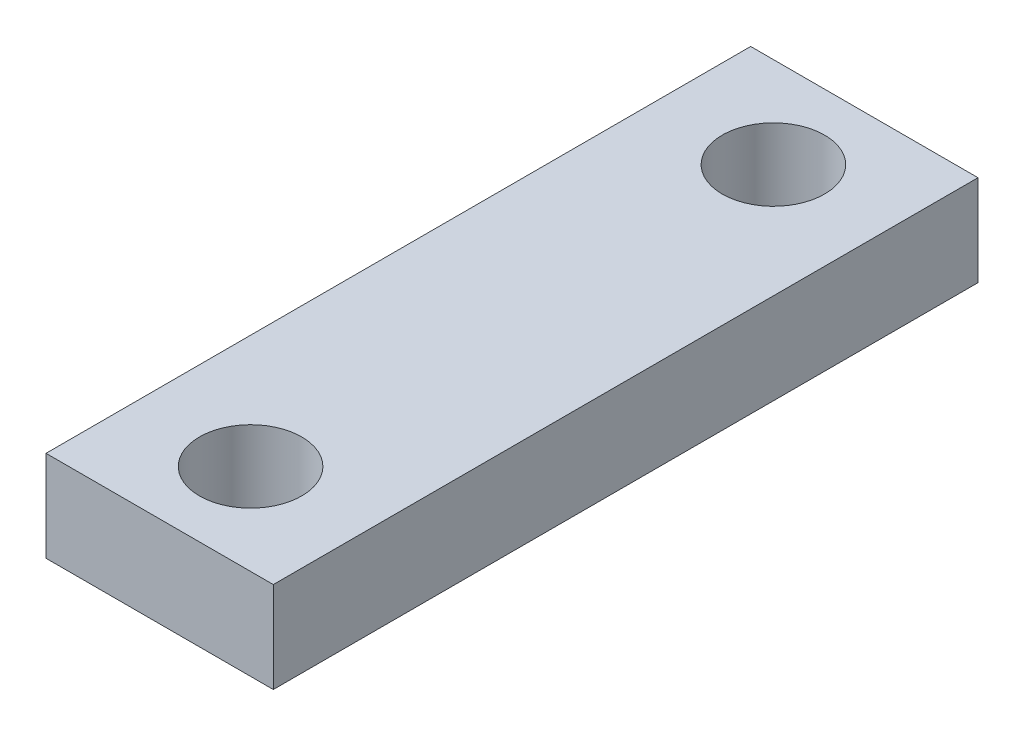
SolidWorks part; units mm, degrees
material "Printed PLA"
ref_plane "Front Plane" through (0, 0, 0) normal (0, 0, 1) x (1, 0, 0)
ref_plane "Top Plane" through (0, 0, 0) normal (0, 1, 0) x (1, 0, 0)
ref_plane "Right Plane" through (0, 0, 0) normal (1, 0, 0) x (0, 0, -1)
sketch "Sketch1" plane through (0, 0, 0) normal (0, 1, 0) x (1, 0, 0)
  line L0 (0, 11.5) -> (0, -11.5) construction
  line L1 (5, -15.5) -> (-5, 15.5) construction
  line L2 (-5, 15.5) -> (5, 15.5)
  line L3 (-5, 15.5) -> (-5, -15.5)
  line L4 (-5, -15.5) -> (5, -15.5)
  line L5 (5, 15.5) -> (5, -15.5)
  circle A0 centre (0, 11.5) radius 2.25
  circle A1 centre (0, -11.5) radius 2.25
  dimension "D2" = 4.5
  dimension "D1" = 23
  dimension "D3" = 10
  dimension "D4" = 31
extrude "Boss-Extrude1" add sketch "Sketch1" along normal blind 4
